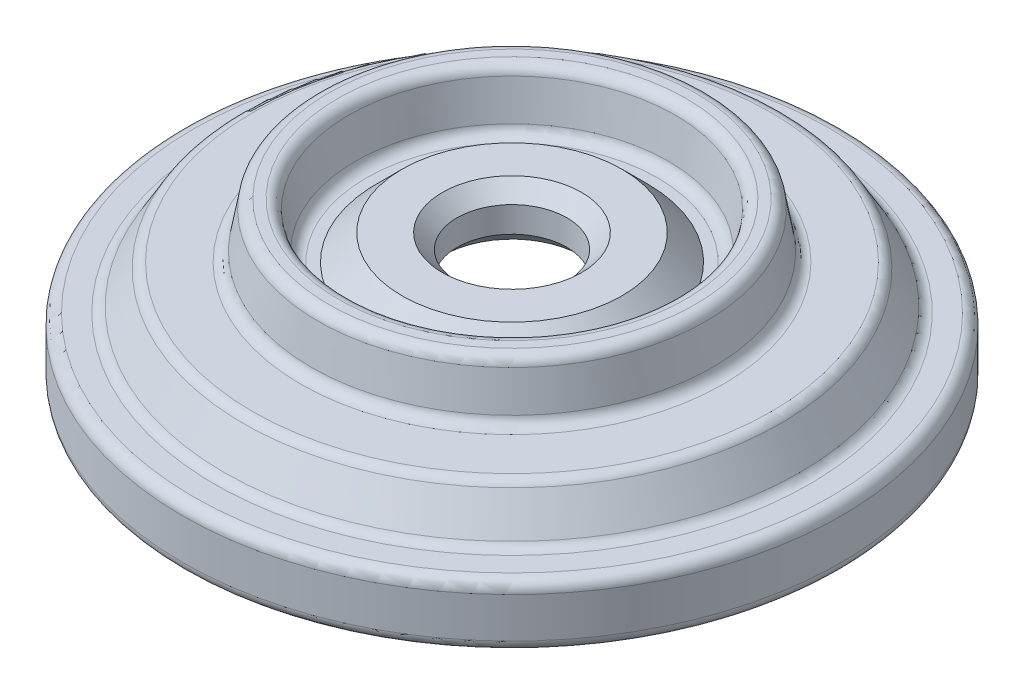
SolidWorks part; units mm, degrees
ref_plane "前视基准面" through (0, 0, 0) normal (0, 0, 1) x (1, 0, 0)
ref_plane "上视基准面" through (0, 0, 0) normal (0, 1, 0) x (1, 0, 0)
ref_plane "右视基准面" through (0, 0, 0) normal (1, 0, 0) x (0, 0, -1)
other "Configuration Table"
sketch "草图1" plane through (0, 0, 0) normal (0, 0, 1) x (1, 0, 0)
  line L0 (-53.1621, 0) -> (53.1621, 0)
  line L1 (0, 0) -> (0, 48.8895) construction
  line L2 (80, 0) -> (68.7417, 19.5)
  line L3 (66.1436, 21) -> (19, 21)
  line L4 (15, 25) -> (15, 32)
  line L5 (19, 36) -> (30, 36)
  line L6 (30, 36) -> (37, 29)
  line L7 (37, 29) -> (39.8162, 29)
  line L8 (42.7707, 31.4791) -> (44.5413, 41.5209)
  line L11 (57.7251, 29) -> (70.7624, 29)
  line L12 (73.3605, 27.5) -> (78.5566, 18.5)
  line L13 (81.1547, 17) -> (87, 17)
  line L14 (90, 14) -> (90, 3)
  line L15 (87, 0) -> (80, 0)
  line L16 (15, 32) -> (19, 36)
  line L17 (19, 21) -> (15, 25)
  line L18 (47.4957, 44) -> (50.0456, 44)
  line L19 (54.7707, 31.4791) -> (53, 41.5209)
  line L21 (48.7707, 44) -> (48.7707, 25.2972) construction
  arc A0 (68.7417, 19.5) -> (66.1436, 21) centre (66.1436, 18) ccw
  arc A1 (39.8162, 29) -> (42.7707, 31.4791) centre (39.8162, 32) ccw
  arc A2 (47.4957, 44) -> (44.5413, 41.5209) centre (47.4957, 41) ccw
  arc A3 (50.0456, 44) -> (53, 41.5209) centre (50.0456, 41) cw
  arc A4 (54.7707, 31.4791) -> (57.7251, 29) centre (57.7251, 32) ccw
  arc A5 (70.7624, 29) -> (73.3605, 27.5) centre (70.7624, 26) cw
  arc A6 (78.5566, 18.5) -> (81.1547, 17) centre (81.1547, 20) ccw
  arc A7 (87, 17) -> (90, 14) centre (87, 14) cw
  arc A8 (90, 3) -> (87, 0) centre (87, 3) cw
  point P4 (0, 0)
  point P10 (15, 21)
  point P11 (15, 36)
  point P22 (56.0441, 15.4146)
  point P45 (43.6815, 31.4791)
  dimension "D19" = 3
  dimension "D1" = 15
  dimension "D2" = 15
  dimension "D3" = 10
  dimension "D6" = 8
  dimension "D7" = 10
  dimension "D8" = 23
  dimension "D9" = 45
  dimension "D10" = 15
  dimension "D11" = 8
  dimension "D12" = 17
  dimension "D13" = 15
  dimension "D14" = 12
  dimension "D15" = 90
  dimension "D16" = 120
  dimension "D17" = 80
  dimension "D18" = 44
revolve "旋转1" add sketch "草图1" angle 360 about L1
